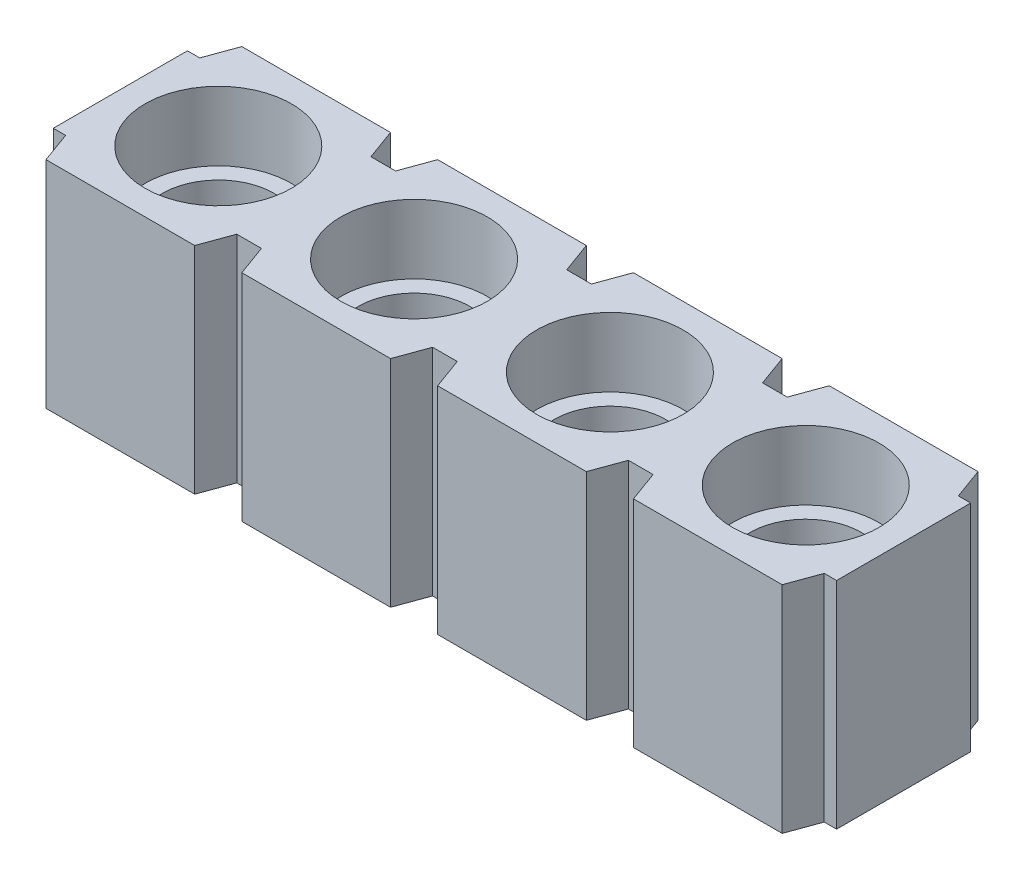
SolidWorks part; units mm, degrees
material "PCT Polyester"
ref_plane "Front Plane" through (0, 0, 0) normal (0, 0, 1) x (1, 0, 0)
ref_plane "Top Plane" through (0, 0, 0) normal (0, 1, 0) x (1, 0, 0)
ref_plane "Right Plane" through (0, 0, 0) normal (1, 0, 0) x (0, 0, -1)
sketch "Sketch1" plane through (0, 0, 0) normal (0, 1, 0) x (1, 0, 0)
  line L0 (9.8544, 0.4) -> (9.6944, 0.4)
  line L1 (9.8544, 2.1399) -> (9.8544, 0.4)
  line L2 (-0.3056, 2.1399) -> (-0.1456, 2.1399)
  line L3 (-0.3056, 2.1399) -> (-0.3056, 0.4)
  line L4 (0, 0) -> (9.5487, 0)
  line L5 (0, 2.54) -> (-0.1456, 2.1399)
  line L6 (0, 0) -> (-0.1456, 0.4)
  line L7 (-0.3056, 0.4) -> (-0.1456, 0.4)
  line L9 (9.5487, 0) -> (9.6944, 0.4)
  line L10 (9.5487, 2.54) -> (9.6944, 2.1399)
  line L11 (9.8544, 2.1399) -> (9.6944, 2.1399)
  line L16 (9.5487, 2.54) -> (0, 2.54)
  dimension "D2" = 2.54
  dimension "D3" = 20
  dimension "D4" = 0.4
  dimension "D5" = 0.4
  dimension "D7" = 0.16
  dimension "INSLENGTH" = 10.16
extrude "Extrude1" add sketch "Sketch1" against normal blind 2.794
hole_wizard "Hole1" positions "3DSketch2" profile "Sketch3" legacy end condition through all
sketch3d "3DSketch2"
  line L2 (-0.3056, 0, -2.1399) -> (-0.3056, 0, -0.4) construction
  line L3 (9.5487, 0, -2.54) -> (0, 0, -2.54) construction
  point P0 (0.9644, 0, -1.27)
  dimension "D1" = 1.27
  dimension "D2" = 1.27
sketch "Sketch3" plane through (0.9644, 0, -1.27) normal (1, 0, 0) x (0, 0, 1)
  line L0 (0, 0) -> (0, 2.794)
  line L1 (0, 2.794) -> (0.7252, 2.794)
  line L2 (0.7252, 2.794) -> (0.7252, 0.8941)
  line L3 (0.7252, 0.8941) -> (0.95, 0.8941)
  line L4 (0.95, 0.8941) -> (0.95, 0)
  line L5 (0.95, 0) -> (0, 0)
  line L6 (0, 110) -> (0, -10) construction
  dimension "Diameter" = 1.4503
  dimension "Depth" = 2.794
  dimension "C-Bore Diameter" = 1.8999
  dimension "C-Bore Depth" = 0.8941
sketch "Sketch4" plane through (0, 0, 0) normal (0, 1, 0) x (1, 0, 0)
  line L0 (1.9288, 0) -> (2.54, 0)
  line L2 (0, 0) -> (9.5487, 0) construction
  line L5 (2.0744, 0.4) -> (1.9288, 0)
  line L6 (2.3944, 0.4) -> (2.54, 0)
  line L7 (9.5487, 2.54) -> (0, 2.54) construction
  line L8 (2.0744, 0.4) -> (2.3944, 0.4)
  line L10 (2.0744, 2.1399) -> (2.3944, 2.1399)
  line L11 (2.3944, 2.1399) -> (2.54, 2.54)
  line L12 (2.0744, 2.1399) -> (1.9288, 2.54)
  line L13 (1.9288, 2.54) -> (2.54, 2.54)
  line L17 (-0.3056, 2.1399) -> (-0.3056, 0.4) construction
  dimension "D1" = 0.4
  dimension "D2" = 0.32
  dimension "D3" = 70
  dimension "D4" = 0.6112
  dimension "D5" = 0.4001
  dimension "D6" = 2.2344
extrude "Extrude2" cut sketch "Sketch4" against normal blind 2.794
pattern_linear "LPattern1" count 4 spacing 2.54 along (1, 0, 0) of "Hole1"
pattern_linear "LPattern2" count 63 spacing 2.54 along (1, 0, 0) of "Extrude2"
